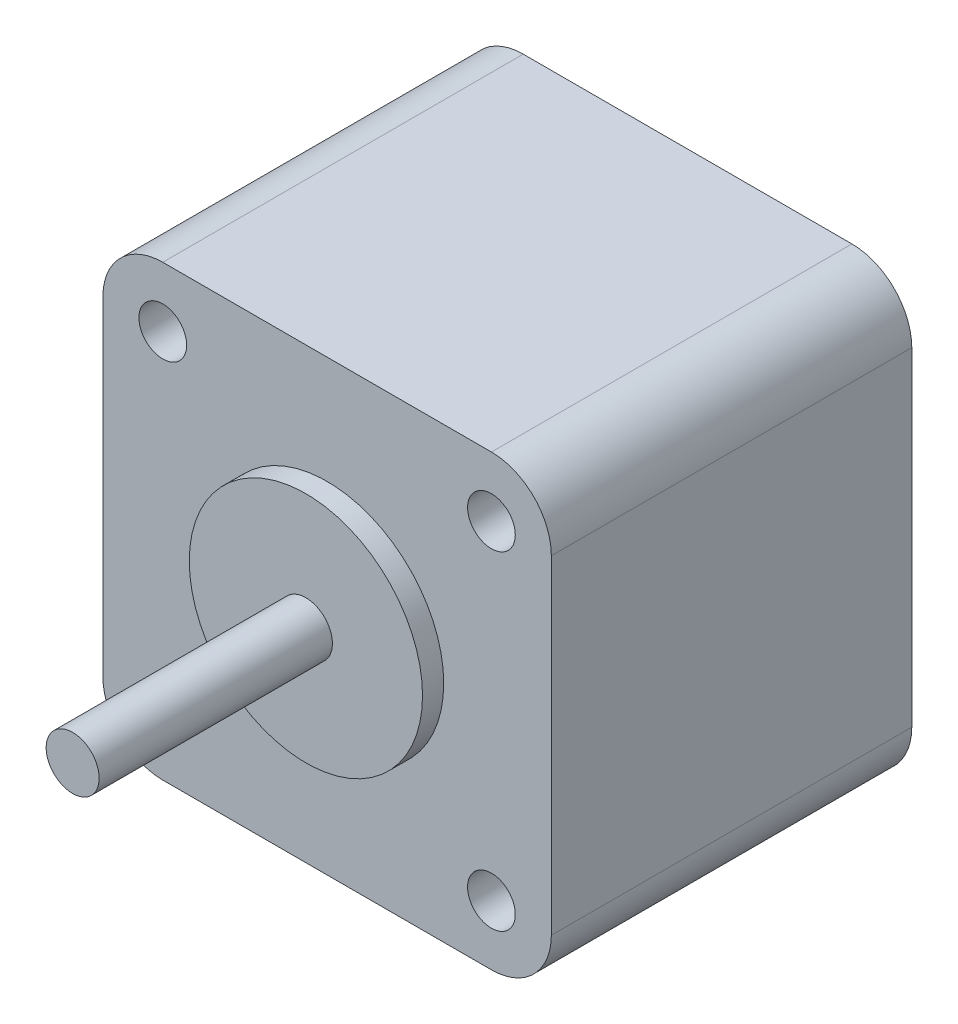
SolidWorks part; units mm, degrees
ref_plane "Front Plane" through (0, 0, 0) normal (0, 0, 1) x (1, 0, 0)
ref_plane "Top Plane" through (0, 0, 0) normal (0, 1, 0) x (1, 0, 0)
ref_plane "Right Plane" through (0, 0, 0) normal (1, 0, 0) x (0, 0, -1)
sketch "Sketch1" plane through (0, 0, 0) normal (0, 0, 1) x (1, 0, 0)
  circle A0 centre (0, 0) radius 2.5
  dimension "D1" = 5
extrude "Boss-Extrude1" add sketch "Sketch1" along normal blind 24
sketch "Sketch2" plane through (0, 0, 0) normal (0, 0, 1) x (1, 0, 0)
  circle A0 centre (0, 0) radius 11
  dimension "D1" = 22
extrude "Boss-Extrude2" add sketch "Sketch2" along normal blind 2
sketch "Sketch4" plane through (0, 0, 0) normal (0, 0, -1) x (-1, 0, 0)
  line L1 (15.5, 21.15) -> (-15.5, 21.15)
  line L2 (21.15, 15.5) -> (21.15, -15.5)
  line L3 (15.5, -21.15) -> (-15.5, -21.15)
  line L4 (-21.15, 15.5) -> (-21.15, -15.5)
  line L5 (21.15, 21.15) -> (-21.15, -21.15) construction
  line L6 (21.15, -21.15) -> (-21.15, 21.15) construction
  arc A0 (21.15, -15.5) -> (15.5, -21.15) centre (15.5, -15.5) cw
  arc A1 (15.5, 21.15) -> (21.15, 15.5) centre (15.5, 15.5) cw
  arc A2 (-15.5, -21.15) -> (-21.15, -15.5) centre (-15.5, -15.5) cw
  arc A3 (-15.5, 21.15) -> (-21.15, 15.5) centre (-15.5, 15.5) ccw
  point P0 (0, 0)
  dimension "D3" = 5.65
  dimension "D4" = 5.65
  dimension "D5" = 5.65
  dimension "D6" = 5.65
  dimension "D1" = 42.3
  dimension "D2" = 42.3
extrude "Boss-Extrude3" add sketch "Sketch4" along normal blind 34 contours L4 A2 L3 A0 L2 A1 L1 A3
sketch "Sketch5" plane through (0, 0, -34) normal (0, 0, -1) x (-1, 0, 0)
  line L0 (-999.5599, 0) -> (49000.4401, 0) construction
  line L1 (0, -999.5599) -> (0, 49000.4401) construction
  line L3 (15.5, -21.15) -> (-15.5, -21.15) construction
  circle A0 centre (-15.5, -15.5) radius 2.25
  circle A1 centre (15.5, -15.5) radius 2.25
  circle A3 centre (-15.5, 15.5) radius 2.25
  circle A4 centre (15.5, 15.5) radius 2.25
  dimension "D1" = 4.5
  dimension "D2" = 5.65
  dimension "D3" = 5.65
  dimension "D4" = 5.65
extrude "Cut-Extrude1" cut sketch "Sketch5" against normal blind 34 contours A3 | A0 | A1 | A4
